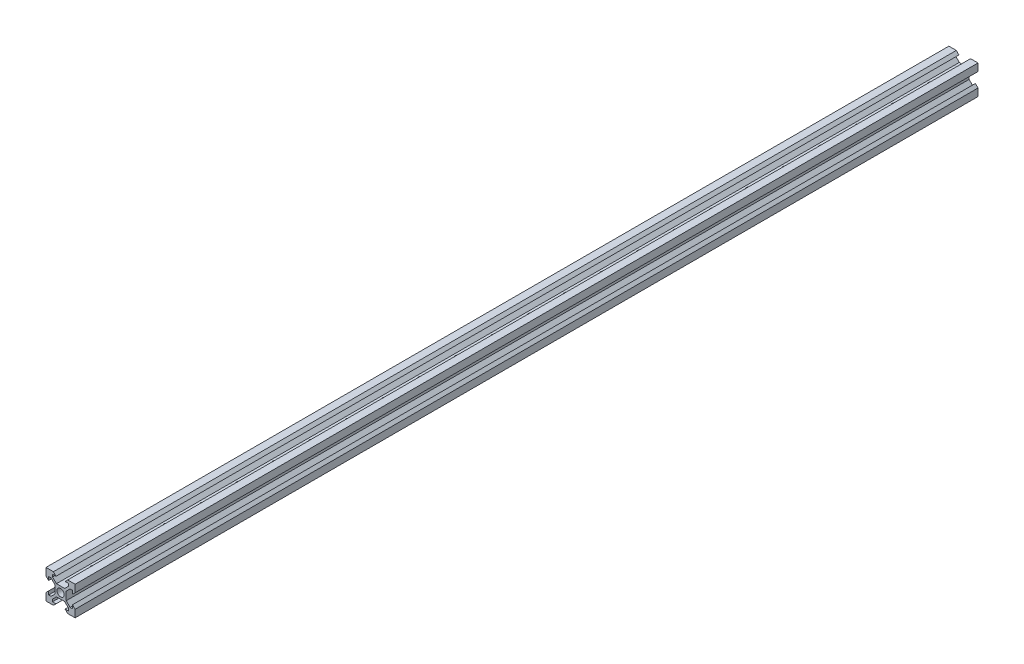
SolidWorks part; units mm, degrees
ref_plane "Front Plane" through (0, 0, 0) normal (0, 0, 1) x (1, 0, 0)
ref_plane "Top Plane" through (0, 0, 0) normal (0, 1, 0) x (1, 0, 0)
ref_plane "Right Plane" through (0, 0, 0) normal (1, 0, 0) x (0, 0, -1)
sketch "Sketch1" plane through (0, 0, 0) normal (0, 0, 1) x (1, 0, 0)
  line L0 (0, 19.8963) -> (0, -21.0662) construction
  line L1 (-23.9511, 0) -> (36.3898, 0) construction
  line L2 (0, 0) -> (-35.2594, 35.2594) construction
  line L3 (0, 0) -> (35.2594, 35.2594) construction
  line L4 (2.8393, 3.9) -> (-2.8393, 3.9)
  line L5 (-2.8393, 3.9) -> (-5.5, 6.5607)
  line L6 (-5.5, 6.5607) -> (-5.5, 8.2)
  line L7 (-5.5, 8.2) -> (-3.1, 8.2)
  line L8 (-3.1, 8.2) -> (-4.9, 10)
  line L9 (-4.9, 10) -> (-10, 10)
  line L10 (-10, 4.9) -> (-10, 10)
  line L11 (-8.2, 3.1) -> (-10, 4.9)
  line L12 (-8.2, 5.5) -> (-8.2, 3.1)
  line L13 (-6.5607, 5.5) -> (-8.2, 5.5)
  line L14 (-3.9, 2.8393) -> (-6.5607, 5.5)
  line L15 (-3.9, -2.8393) -> (-3.9, 2.8393)
  line L16 (3.1, 8.2) -> (4.9, 10)
  line L17 (5.5, 8.2) -> (3.1, 8.2)
  line L18 (4.9, 10) -> (10, 10)
  line L19 (10, 4.9) -> (10, 10)
  line L20 (8.2, 3.1) -> (10, 4.9)
  line L21 (8.2, 5.5) -> (8.2, 3.1)
  line L22 (6.5607, 5.5) -> (8.2, 5.5)
  line L23 (5.5, 6.5607) -> (5.5, 8.2)
  line L24 (2.8393, 3.9) -> (5.5, 6.5607)
  line L25 (3.9, 2.8393) -> (6.5607, 5.5)
  line L26 (3.9, -2.8393) -> (3.9, 2.8393)
  line L27 (-3.9, -2.8393) -> (-6.5607, -5.5)
  line L28 (-6.5607, -5.5) -> (-8.2, -5.5)
  line L29 (-8.2, -5.5) -> (-8.2, -3.1)
  line L30 (-8.2, -3.1) -> (-10, -4.9)
  line L31 (-10, -4.9) -> (-10, -10)
  line L32 (-4.9, -10) -> (-10, -10)
  line L33 (-3.1, -8.2) -> (-4.9, -10)
  line L34 (-5.5, -6.5607) -> (-5.5, -8.2)
  line L35 (-5.5, -8.2) -> (-3.1, -8.2)
  line L36 (-2.8393, -3.9) -> (-5.5, -6.5607)
  line L37 (2.8393, -3.9) -> (-2.8393, -3.9)
  line L38 (2.8393, -3.9) -> (5.5, -6.5607)
  line L39 (3.9, -2.8393) -> (6.5607, -5.5)
  line L40 (6.5607, -5.5) -> (8.2, -5.5)
  line L41 (5.5, -6.5607) -> (5.5, -8.2)
  line L42 (5.5, -8.2) -> (3.1, -8.2)
  line L43 (3.1, -8.2) -> (4.9, -10)
  line L44 (4.9, -10) -> (10, -10)
  line L45 (10, -4.9) -> (10, -10)
  line L46 (8.2, -5.5) -> (8.2, -3.1)
  line L47 (8.2, -3.1) -> (10, -4.9)
  circle A0 centre (0, 0) radius 2.5
  point P37 (0, 3.9)
  point P40 (-3.9, 0)
  point P53 (3.9, 0)
  dimension "D2" = 5
  dimension "D1" = 6.2
  dimension "D3" = 1.8
  dimension "D4" = 11
  dimension "D5" = 45
  dimension "D6" = 6.1
  dimension "D7" = 1.5
  dimension "D8" = 20
extrude "Boss-Extrude1" add sketch "Sketch1" along normal blind 620
sketch "Sketch2" plane through (0, 3.9, 0) normal (0, 1, 0) x (1, 0, 0)
  line L0 (0, 0) -> (0, -620) construction
  line L2 (2.8393, -620) -> (-2.8393, -620) construction
  line L3 (0, -310) -> (53.669, -310) construction
  circle A17 centre (0, -297.5) radius 1.5
  dimension "D1" = 3
  dimension "D2" = 12.5
extrude "Cut-Extrude1" cut sketch "Sketch2" against normal blind 10
pattern_linear "LPattern1" count 13 spacing 25 along (0, 0, 1) count 13 spacing 25 along (0, 0, -1) of "Cut-Extrude1"
